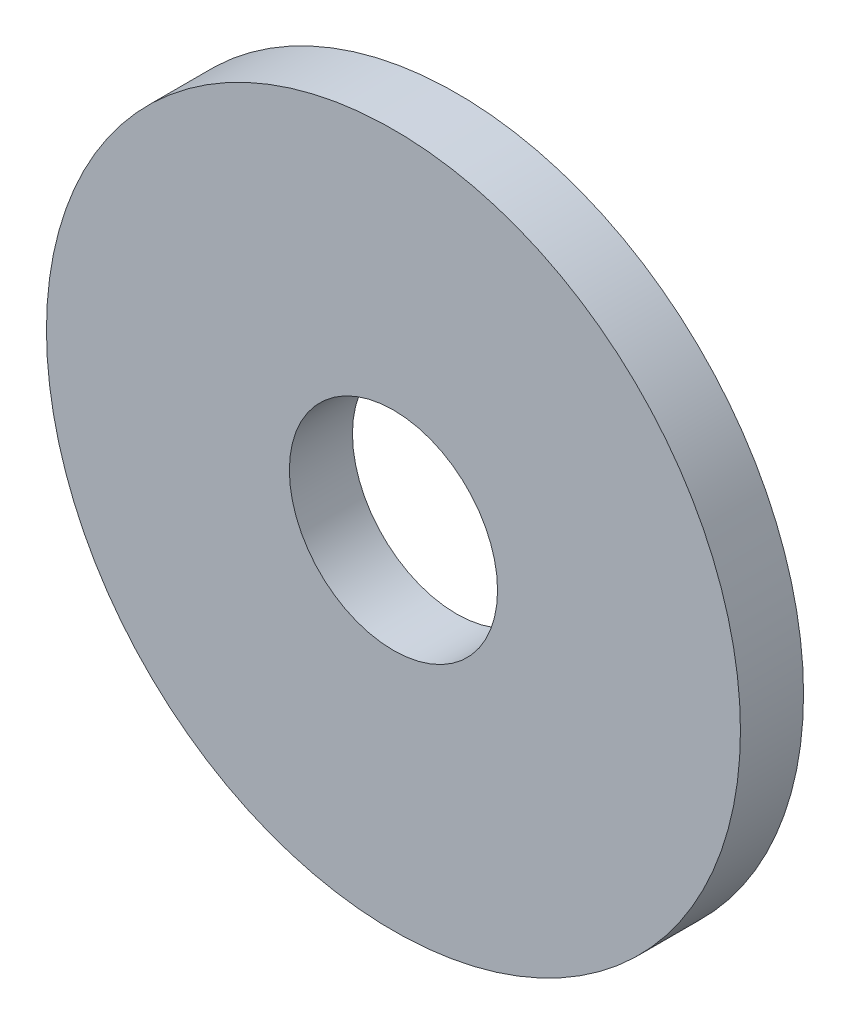
SolidWorks part; units mm, degrees
material "AISI 316 Stainless Steel Sheet (SS)"
ref_plane "Front Plane" through (0, 0, 0) normal (0, 0, 1) x (1, 0, 0)
ref_plane "Top Plane" through (0, 0, 0) normal (0, 1, 0) x (1, 0, 0)
ref_plane "Right Plane" through (0, 0, 0) normal (1, 0, 0) x (0, 0, -1)
sketch "Sketch1" plane through (0, 0, 0) normal (0, 0, 1) x (1, 0, 0)
  line L0 (-11, 0) -> (11, 0) construction
  line L1 (0, -11) -> (0, 11) construction
  circle A0 centre (0, 0) radius 11
  circle A1 centre (0, 0) radius 3.3
  point P4 (0, 0)
  point P9 (0, 0)
  point P10 (0, -3.3)
  point P12 (-11, 0)
  point P13 (0, -11)
  dimension "ID" = 6.6
  dimension "OD" = 22
sketch "Sketch2" plane through (0, 0, 0) normal (1, 0, 0) x (0, 0, -1)
  line L0 (1, -11) -> (-1, -11) construction
  point P5 (0, -11)
  dimension "Thickness" = 2
sketch "Sketch3" plane through (0, 0, 0) normal (0, 0, 1) x (1, 0, 0)
  line L0 (0, -11) -> (0, 11) construction
  circle A0 centre (0, 0) radius 11
  circle A1 centre (0, 0) radius 3.3
  circle A2 centre (0, 0) radius 3.3 construction
extrude "Boss-Extrude1" add sketch "Sketch3" along normal mid plane 2
equation "\"D1@Boss-Extrude1\" = \"Thickness@Sketch2\""
